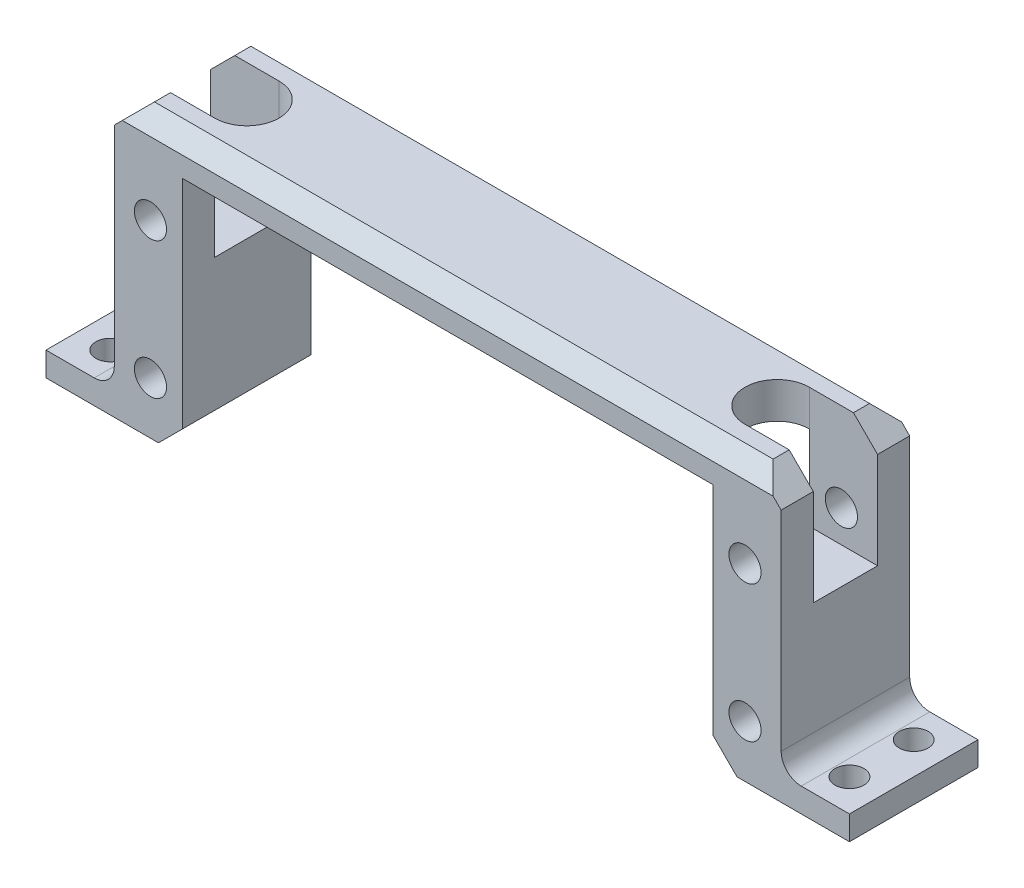
SolidWorks part; units mm, degrees
other "Markup1"
sketch "Sketch6" plane through (-36, 25, 8) normal (-0.8707, 0.2235, 0.4381) x (0.4473, -0.0107, 0.8943)
material "Nylon PA 12"
ref_plane "Front Plane" through (0, 0, 0) normal (0, 0, 1) x (1, 0, 0)
ref_plane "Top Plane" through (0, 0, 0) normal (0, 1, 0) x (1, 0, 0)
ref_plane "Right Plane" through (0, 0, 0) normal (1, 0, 0) x (0, 0, -1)
sketch "Sketch1" plane through (0, 0, 0) normal (0, 0, 1) x (1, 0, 0)
  line L0 (-50, 0) -> (-33, 0)
  line L1 (-33, 0) -> (-33, 30)
  line L2 (-33, 30) -> (33, 30)
  line L3 (33, 30) -> (33, 0)
  line L4 (33, 0) -> (50, 0)
  line L5 (-50, 0) -> (-50, 3)
  line L6 (-50, 3) -> (-41.5, 3)
  line L7 (50, 0) -> (50, 3)
  line L8 (50, 3) -> (41.5, 3)
  line L9 (-41.5, 3) -> (-41.5, 34.5)
  line L10 (-41.5, 34.5) -> (41.5, 34.5)
  line L11 (41.5, 34.5) -> (41.5, 3)
  dimension "D1" = 100
  dimension "D2" = 17
  dimension "D3" = 66
  dimension "D4" = 33
  dimension "D5" = 30
  dimension "D6" = 3
  dimension "D7" = 17
  dimension "D8" = 4.5
  dimension "D9" = 8.5
  dimension "D10" = 8.5
extrude "Boss-Extrude1" add sketch "Sketch1" along normal mid plane 16
chamfer "Chamfer5" distance 3 angle 45 4 edges at (-41.5, 34.5, 0) (33, 0, 0) (-33, 0, 0) (41.5, 34.5, 0)
fillet "Fillet1" radius 2.5 2 edges at (41.5, 3, 0) (-41.5, 3, 0)
sketch "Sketch2" plane through (0, 0, 8) normal (0, 0, 1) x (1, 0, 0)
  line L2 (37, 37.1974) -> (37, -3.6862) construction
  circle A2 centre (37, 23.5) radius 2
  circle A3 centre (37, 6.5) radius 2
  dimension "D1" = 37
  dimension "D4" = 4
  dimension "D2" = 6.5
  dimension "D3" = 17
extrude "Cut-Extrude1" cut sketch "Sketch2" against normal through all
mirror "Mirror1" about plane through (0, 0, 0) normal (1, 0, 0) of "Cut-Extrude1"
sketch "Sketch3" plane through (0, 3, 0) normal (0, 1, 0) x (1, 0, 0)
  line L0 (50, -8) -> (50, 8) construction
  line L1 (44, 28.8859) -> (44, -25.0715) construction
  line L2 (-44, 27.8941) -> (-44, -24.0796) construction
  line L3 (-44, -8) -> (-44, 8) construction
  line L4 (44, 8) -> (44, -8) construction
  line L5 (56.6832, -8) -> (-41.1826, -8) construction
  line L6 (65.7079, 8) -> (-46.658, 8) construction
  line L7 (50, 8) -> (44, 8) construction
  line L8 (50, -8) -> (44, -8) construction
  line L9 (50, 29.9064) -> (50, -19.7738) construction
  circle A0 centre (46, 4) radius 1.8
  circle A1 centre (46, -4) radius 1.8
  circle A2 centre (-46, 4) radius 1.8
  circle A3 centre (-46, -4) radius 1.8
  dimension "D2" = 3.6
  dimension "D3" = 3.6
  dimension "D12" = 3.6
  dimension "D14" = 3.6
  dimension "D1" = 2
  dimension "D4" = 16
  dimension "D5" = 4
  dimension "D6" = 4
  dimension "D7" = 6
  dimension "D8" = 2
  dimension "D9" = 4
  dimension "D10" = 12
  dimension "D11" = 16
  dimension "D13" = 4
  dimension "D15" = 88
extrude "Cut-Extrude2" cut sketch "Sketch3" against normal through all
sketch "Sketch5" plane through (0, 34.5, 0) normal (0, 1, 0) x (1, 0, 0)
  line L0 (-41.5, -8) -> (-41.5, 8) construction
  line L6 (-46, 4) -> (-41.5, 4) construction
  line L7 (46, 4) -> (46, -4) construction
  line L8 (46, -4) -> (41.5, -4) construction
  line L9 (-46, -4) -> (-46, 4) construction
  line L13 (41.5, 8) -> (41.5, -8) construction
  line L18 (-41.5, -4) -> (-46, -4) construction
  line L21 (41.5, 4) -> (46, 4) construction
  line L32 (33, -8) -> (33, 8) construction
  line L33 (41.5, 4) -> (33, 4)
  line L34 (41.5, 4) -> (41.5, -4)
  line L35 (41.5, -4) -> (33, -4)
  line L36 (33, 4) -> (33, -4)
  line L37 (-33, -8) -> (-33, 8) construction
  line L38 (-41.5, 4) -> (-33, 4)
  line L39 (-41.5, 4) -> (-41.5, -4)
  line L40 (-41.5, -4) -> (-33, -4)
  line L41 (-33, 4) -> (-33, -4)
extrude "Cut-Extrude3" cut sketch "Sketch5" against normal blind 15
sketch "Sketch7" plane through (0, 34.5, 0) normal (0, 1, 0) x (1, 0, 0)
  line L0 (-38.5, 4) -> (-38.5, -4) construction
  line L1 (-33, -4) -> (-33, 4) construction
  line L2 (33, 4) -> (33, -4) construction
  line L3 (33, 4) -> (33, -4)
  line L4 (-33, 4) -> (-33, -4)
  arc A0 (-33, -4) -> (-33, 4) centre (-33, 0) ccw
  arc A1 (33, 4) -> (33, -4) centre (33, 0) ccw
extrude "Cut-Extrude5" cut sketch "Sketch7" against normal blind 15
chamfer "Chamfer6" distance 2 angle 45 2 edges at (0, 34.5, -8) (0, 34.5, 8)
sketch "Sketch8" plane through (0, 0, 8) normal (0, 0, 1) x (1, 0, 0)
  line L0 (-37, 23.5) -> (-37, -4.3269) construction
  line L1 (37, 23.5) -> (37, -7.2946) construction
